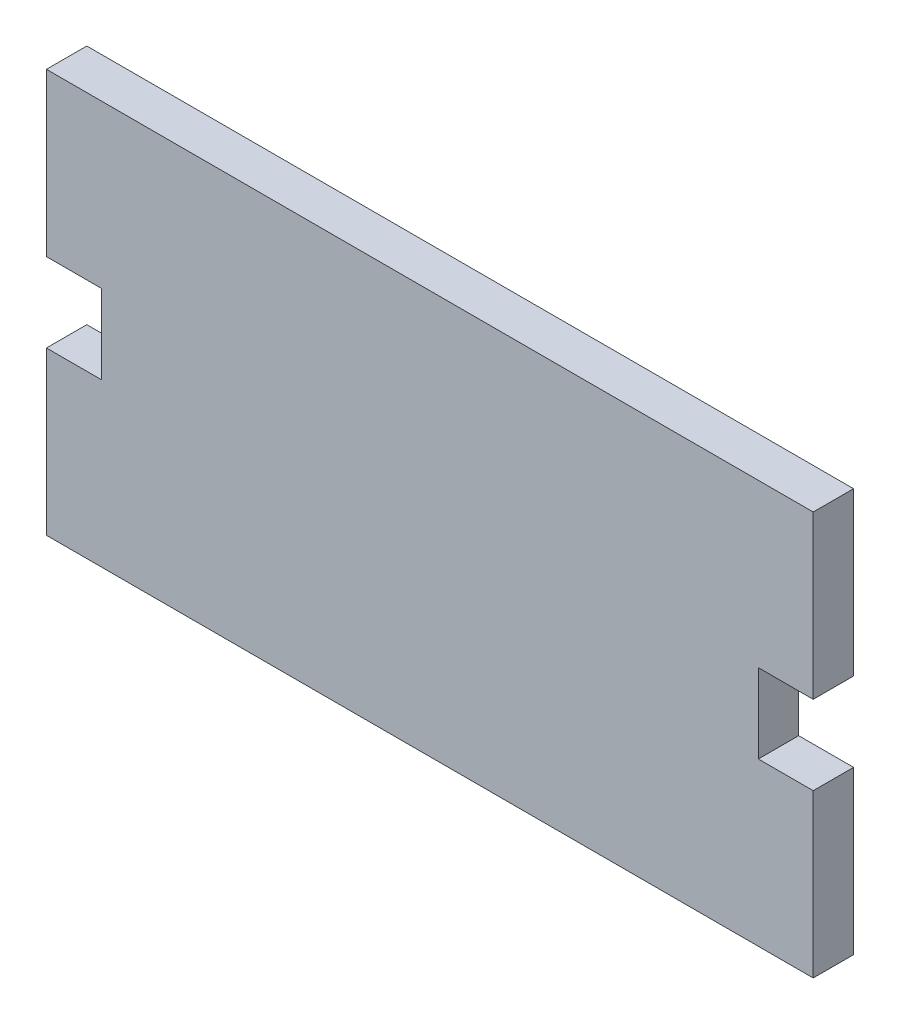
SolidWorks part; units mm, degrees
ref_plane "Front Plane" through (0, 0, 0) normal (0, 0, 1) x (1, 0, 0)
ref_plane "Top Plane" through (0, 0, 0) normal (0, 1, 0) x (1, 0, 0)
ref_plane "Right Plane" through (0, 0, 0) normal (1, 0, 0) x (0, 0, -1)
sketch "Sketch1" plane through (0, 0, 0) normal (0, 0, 1) x (1, 0, 0)
  line L1 (0, 0) -> (120.65, 0)
  line L2 (0, 0) -> (0, 63.5)
  line L3 (0, 63.5) -> (120.65, 63.5)
  line L4 (120.65, 0) -> (120.65, 63.5)
  dimension "D1" = 63.5
  dimension "D2" = 120.65
extrude "Boss-Extrude1" add sketch "Sketch1" along normal blind 6.35
sketch "Sketch2" plane through (0, 0, 6.35) normal (0, 0, 1) x (1, 0, 0)
  line L0 (0, 63.5) -> (0, 0) construction
  line L1 (0, 37.973) -> (8.636, 37.973)
  line L2 (0, 37.973) -> (0, 25.527)
  line L3 (0, 25.527) -> (8.636, 25.527)
  line L4 (8.636, 37.973) -> (8.636, 25.527)
  line L5 (60.325, 63.5) -> (60.325, 0) construction
  line L6 (120.65, 63.5) -> (0, 63.5) construction
  line L7 (0, 0) -> (120.65, 0) construction
  line L8 (120.65, 25.527) -> (112.014, 25.527)
  line L9 (112.014, 37.973) -> (112.014, 25.527)
  line L10 (120.65, 37.973) -> (112.014, 37.973)
  line L11 (120.65, 37.973) -> (120.65, 25.527)
  point P4 (0, 31.75)
  dimension "D1" = 12.446
  dimension "D2" = 8.636
extrude "Cut-Extrude1" cut sketch "Sketch2" against normal blind 6.35
